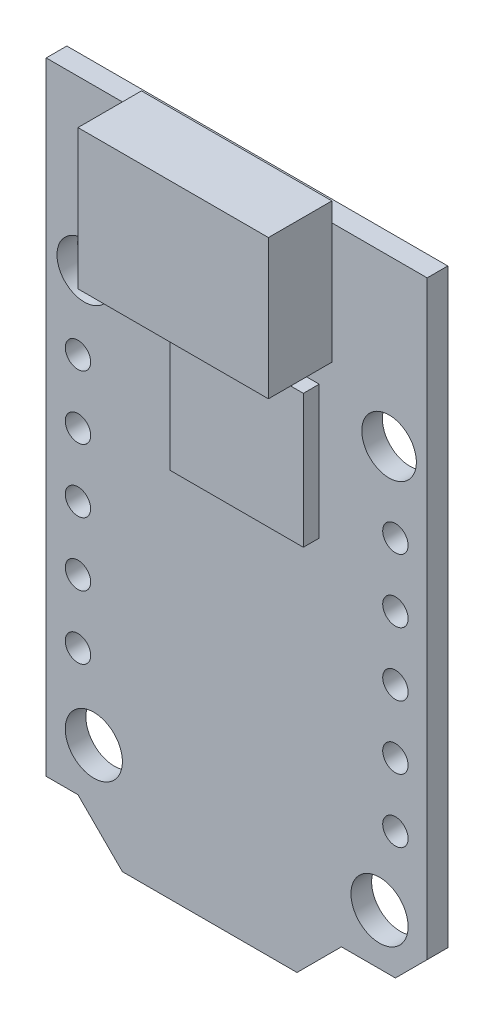
SolidWorks part; units mm, degrees
ref_plane "Front Plane" through (0, 0, 0) normal (0, 0, 1) x (1, 0, 0)
ref_plane "Top Plane" through (0, 0, 0) normal (0, 1, 0) x (1, 0, 0)
ref_plane "Right Plane" through (0, 0, 0) normal (1, 0, 0) x (0, 0, -1)
sketch "Sketch1" plane through (0, 0, 0) normal (0, 0, 1) x (1, 0, 0)
  line L0 (1.905, 3.81) -> (13.335, 3.81) construction
  line L1 (0, 0) -> (15.24, 0) construction
  line L2 (0, 0) -> (0, 26.67) construction
  line L3 (0, 26.67) -> (15.24, 26.67)
  line L4 (15.24, 0) -> (15.24, 26.67) construction
  line L5 (7.62, 3.81) -> (7.62, 0) construction
  line L6 (1.27, 6.858) -> (1.27, 9.398) construction
  line L7 (1.27, 9.398) -> (1.27, 11.938) construction
  line L8 (1.27, 11.938) -> (1.27, 14.478) construction
  line L9 (1.27, 14.478) -> (1.27, 17.018) construction
  line L10 (13.97, 6.858) -> (13.97, 9.398) construction
  line L11 (13.97, 9.398) -> (13.97, 11.938) construction
  line L12 (13.97, 11.938) -> (13.97, 14.478) construction
  line L13 (13.97, 14.478) -> (13.97, 17.018) construction
  line L14 (1.27, 6.858) -> (13.97, 6.858) construction
  line L15 (7.62, 6.858) -> (7.62, 3.81) construction
  line L16 (1.524, 20.066) -> (13.716, 20.066) construction
  line L17 (7.62, 26.67) -> (7.62, 20.066) construction
  line L18 (1.27, 17.018) -> (13.97, 17.018) construction
  line L19 (7.62, 17.018) -> (7.62, 20.066) construction
  line L20 (0, 1.778) -> (1.27, 1.778)
  line L21 (1.27, 1.778) -> (3.048, 0)
  line L22 (3.048, 0) -> (10.033, 0)
  line L23 (10.033, 0) -> (11.811, 1.778)
  line L24 (11.811, 1.778) -> (13.97, 1.778)
  line L25 (13.97, 1.778) -> (15.24, 3.048)
  line L26 (15.24, 26.67) -> (15.24, 3.048)
  line L27 (0, 26.67) -> (0, 1.778)
  circle A0 centre (1.905, 3.81) radius 1.143
  circle A1 centre (13.335, 3.81) radius 1.143
  circle A2 centre (1.27, 6.858) radius 0.508
  circle A3 centre (1.27, 9.398) radius 0.508
  circle A4 centre (1.27, 11.938) radius 0.508
  circle A5 centre (1.27, 14.478) radius 0.508
  circle A6 centre (1.27, 17.018) radius 0.508
  circle A7 centre (13.97, 17.018) radius 0.508
  circle A8 centre (13.97, 14.478) radius 0.508
  circle A9 centre (13.97, 11.938) radius 0.508
  circle A10 centre (13.97, 9.398) radius 0.508
  circle A11 centre (13.97, 6.858) radius 0.508
  circle A12 centre (1.524, 20.066) radius 1.0922
  circle A13 centre (13.716, 20.066) radius 1.0922
  dimension "D3" = 1.016
  dimension "D4" = 2.286
  dimension "D5" = 2.286
  dimension "D11" = 2.1844
  dimension "D1" = 15.24
  dimension "D2" = 26.67
  dimension "D6" = 3.81
  dimension "D7" = 11.43
  dimension "D8" = 2.54
  dimension "D9" = 2.54
  dimension "D10" = 12.7
  dimension "D12" = 6.604
  dimension "D13" = 12.192
  dimension "D14" = 6.985
  dimension "D15" = 1.778
  dimension "D16" = 135
  dimension "D17" = 135
  dimension "D18" = 1.27
  dimension "D19" = 45
  dimension "D20" = 1.27
extrude "Boss-Extrude1" add sketch "Sketch1" along normal blind 0.8255
sketch "Sketch2" plane through (0, 0, 0.8255) normal (0, 0, 1) x (1, 0, 0)
  line L0 (7.62, 27.432) -> (7.62, 26.67) construction
  line L1 (3.81, 27.432) -> (11.43, 27.432)
  line L2 (3.81, 27.432) -> (3.81, 21.844)
  line L3 (3.81, 21.844) -> (11.43, 21.844)
  line L4 (11.43, 27.432) -> (11.43, 21.844)
  line L5 (15.24, 26.67) -> (0, 26.67) construction
  dimension "D1" = 7.62
  dimension "D2" = 5.588
  dimension "D3" = 0.762
extrude "Boss-Extrude2" add sketch "Sketch2" along normal blind 2.54
sketch "Sketch3" plane through (0, 0, 0.8255) normal (0, 0, 1) x (1, 0, 0)
  line L0 (11.43, 21.844) -> (11.43, 26.67) construction
  line L1 (5.588, 20.828) -> (10.922, 20.828)
  line L2 (5.588, 20.828) -> (5.588, 15.494)
  line L3 (5.588, 15.494) -> (10.922, 15.494)
  line L4 (10.922, 20.828) -> (10.922, 15.494)
  line L5 (3.81, 21.844) -> (11.43, 21.844) construction
  dimension "D1" = 5.334
  dimension "D2" = 5.334
  dimension "D3" = 0.508
  dimension "D4" = 1.016
extrude "Boss-Extrude3" add sketch "Sketch3" along normal blind 0.635
